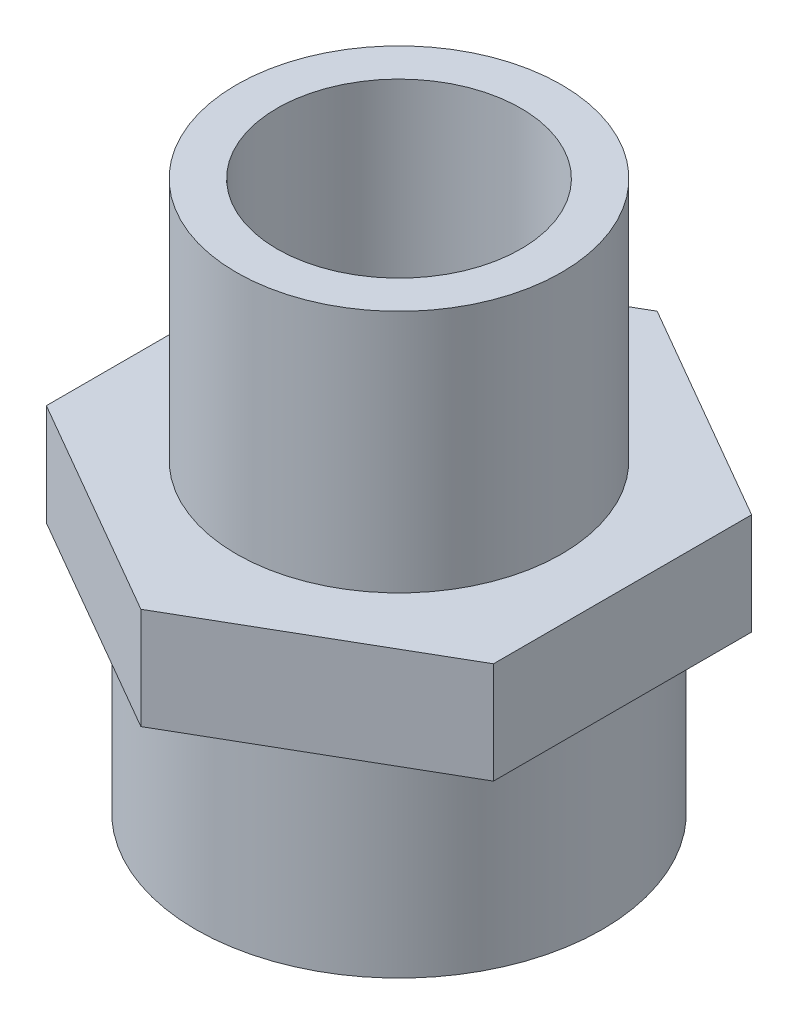
SolidWorks part; units mm, degrees
material "Brass"
ref_plane "Front" through (0, 0, 0) normal (0, 0, 1) x (1, 0, 0)
ref_plane "Top" through (0, 0, 0) normal (0, 1, 0) x (1, 0, 0)
ref_plane "Right" through (0, 0, 0) normal (1, 0, 0) x (0, 0, -1)
sketch "Sketch1" plane through (0, 0, 0) normal (0, 1, 0) x (1, 0, 0)
  circle A0 centre (0, 0) radius 10.16
  dimension "D1" = 20.32
extrude "Boss-Extrude1" add sketch "Sketch1" along normal blind 15.24
sketch "Sketch2" plane through (0, 0, 0) normal (0, -1, 0) x (1, 0, 0)
  line L1 (-13.97, -8.0656) -> (0, -16.1312)
  line L2 (0, -16.1312) -> (13.97, -8.0656)
  line L3 (13.97, -8.0656) -> (13.97, 8.0656)
  line L4 (13.97, 8.0656) -> (0, 16.1312)
  line L5 (0, 16.1312) -> (-13.97, 8.0656)
  line L6 (-13.97, 8.0656) -> (-13.97, -8.0656)
  circle A0 centre (0, 0) radius 13.97 construction
  dimension "D1" = 27.94
extrude "Boss-Extrude2" add sketch "Sketch2" along normal blind 6.35
sketch "Sketch3" plane through (0, -6.35, 0) normal (0, -1, 0) x (1, 0, 0)
  circle A0 centre (0, 0) radius 12.7
  dimension "D1" = 25.4
extrude "Boss-Extrude3" add sketch "Sketch3" along normal blind 12.7
sketch "Sketch4" plane through (0, 15.24, 0) normal (0, 1, 0) x (1, 0, 0)
  circle A0 centre (0, 0) radius 7.62
  dimension "D1" = 15.24
extrude "Cut-Extrude1" cut sketch "Sketch4" against normal through all
